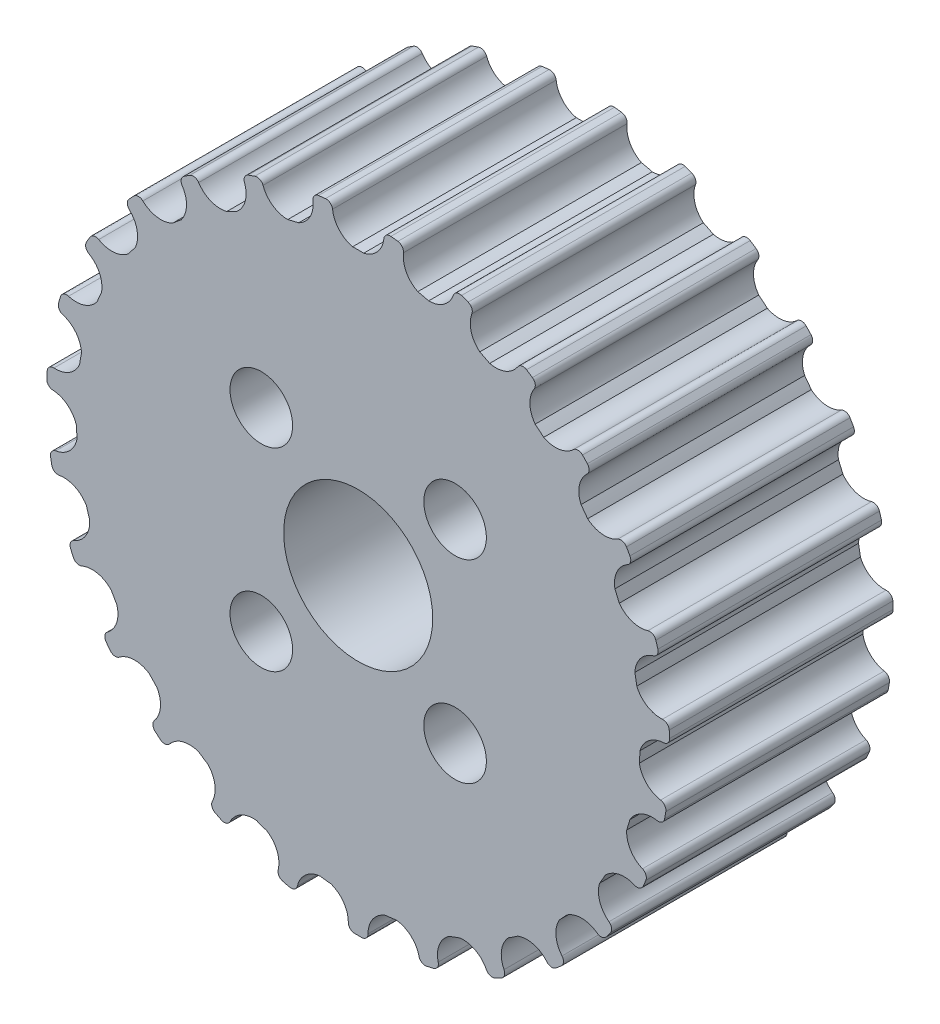
SolidWorks part; units mm, degrees
material "ABS"
ref_plane "Front Plane" through (0, 0, 0) normal (0, 0, 1) x (1, 0, 0)
ref_plane "Top Plane" through (0, 0, 0) normal (0, 1, 0) x (1, 0, 0)
ref_plane "Right Plane" through (0, 0, 0) normal (1, 0, 0) x (0, 0, -1)
ref_plane "Plane1" through (0, 0, 7.5) normal (0, 0, 1) x (1, 0, 0)
sketch "Sketch1" plane through (0, 0, 7.5) normal (0, 0, 1) x (1, 0, 0)
  arc A0 (-2.1927, 20.7989) -> (-2.663, 20.7439) centre (0, 0) ccw
  arc A1 (-2.663, 20.7439) -> (-3.0351, 20.266) centre (-2.6082, 20.3174) ccw
  arc A2 (-3.0351, 20.266) -> (-3.9982, 18.4886) centre (-4.7708, 20.0568) cw
  arc A3 (-3.9982, 18.4886) -> (-4.7247, 18.3164) centre (0, 0) ccw
  arc A4 (-4.7247, 18.3164) -> (-6.3831, 19.4725) centre (-4.7381, 20.0646) cw
  arc A5 (-6.3831, 19.4725) -> (-6.9301, 19.7326) centre (-6.7876, 19.3269) ccw
  arc A6 (-6.9301, 19.7326) -> (-7.3751, 19.5706) centre (0, 0) ccw
  arc A7 (-7.3751, 19.5706) -> (-7.627, 19.0198) centre (-7.2234, 19.1683) ccw
  arc A8 (-7.627, 19.0198) -> (-8.1542, 17.0682) centre (-9.2676, 18.416) cw
  arc A9 (-8.1542, 17.0682) -> (-8.8214, 16.7331) centre (0, 0) ccw
  arc A10 (-8.8214, 16.7331) -> (-10.7017, 17.4756) centre (-9.2376, 18.431) cw
  arc A11 (-10.7017, 17.4756) -> (-11.294, 17.6025) centre (-11.0618, 17.2406) ccw
  arc A12 (-11.294, 17.6025) -> (-11.6896, 17.3423) centre (0, 0) ccw
  arc A13 (-11.6896, 17.3423) -> (-11.8077, 16.7482) centre (-11.4492, 16.9857) ccw
  arc A14 (-11.8077, 16.7482) -> (-11.8706, 14.7276) centre (-13.2649, 15.7823) cw
  arc A15 (-11.8706, 14.7276) -> (-12.4425, 14.2477) centre (0, 0) ccw
  arc A16 (-12.4425, 14.2477) -> (-14.4433, 14.5366) centre (-13.2391, 15.8039) cw
  arc A17 (-14.4433, 14.5366) -> (-15.049, 14.5235) centre (-14.7395, 14.2248) ccw
  arc A18 (-15.049, 14.5235) -> (-15.3739, 14.179) centre (0, 0) ccw
  arc A19 (-15.3739, 14.179) -> (-15.3518, 13.5737) centre (-15.0578, 13.8875) ccw
  arc A20 (-15.3518, 13.5737) -> (-14.947, 11.5931) centre (-16.5469, 12.2978) cw
  arc A21 (-14.947, 11.5931) -> (-15.3929, 10.9942) centre (0, 0) ccw
  arc A22 (-15.3929, 10.9942) -> (-17.4064, 10.8139) centre (-16.5269, 12.3248) cw
  arc A23 (-17.4064, 10.8139) -> (-17.9926, 10.6614) centre (-17.6227, 10.4422) ccw
  arc A24 (-17.9926, 10.6614) -> (-18.2294, 10.2514) centre (0, 0) ccw
  arc A25 (-18.2294, 10.2514) -> (-18.0683, 9.6674) centre (-17.8546, 10.0406) ccw
  arc A26 (-18.0683, 9.6674) -> (-17.2177, 7.8335) centre (-18.937, 8.1503) cw
  arc A27 (-17.2177, 7.8335) -> (-17.5134, 7.148) centre (0, 0) ccw
  arc A28 (-17.5134, 7.148) -> (-19.431, 6.5082) centre (-18.9237, 8.1812) cw
  arc A29 (-19.431, 6.5082) -> (-19.9664, 6.2247) centre (-19.5558, 6.0967) ccw
  arc A30 (-19.9664, 6.2247) -> (-20.1022, 5.7711) centre (0, 0) ccw
  arc A31 (-20.1022, 5.7711) -> (-19.8107, 5.24) centre (-19.6889, 5.6524) ccw
  arc A32 (-19.8107, 5.24) -> (-18.5601, 3.6517) centre (-20.3061, 3.5635) cw
  arc A33 (-18.5601, 3.6517) -> (-18.6898, 2.9164) centre (0, 0) ccw
  arc A34 (-18.6898, 2.9164) -> (-20.4082, 1.8516) centre (-20.3003, 3.5966) cw
  arc A35 (-20.4082, 1.8516) -> (-20.8637, 1.4523) centre (-20.4347, 1.4225) ccw
  arc A36 (-20.8637, 1.4523) -> (-20.8912, 0.9796) centre (0, 0) ccw
  arc A37 (-20.8912, 0.9796) -> (-20.4851, 0.5301) centre (-20.4617, 0.9595) ccw
  arc A38 (-20.4851, 0.5301) -> (-18.902, -0.727) centre (-20.5806, -1.2155) cw
  arc A39 (-18.902, -0.727) -> (-18.8586, -1.4723) centre (0, 0) ccw
  arc A40 (-18.8586, -1.4723) -> (-20.2851, -2.9047) centre (-20.5825, -1.182) cw
  arc A41 (-20.2851, -2.9047) -> (-20.6362, -3.3983) centre (-20.2119, -3.3284) ccw
  arc A42 (-20.6362, -3.3983) -> (-20.554, -3.8646) centre (0, 0) ccw
  arc A43 (-20.554, -3.8646) -> (-20.0552, -4.2084) centre (-20.1314, -3.7852) ccw
  arc A44 (-20.0552, -4.2084) -> (-18.2248, -5.0665) centre (-19.7455, -5.929) cw
  arc A45 (-18.2248, -5.0665) -> (-18.0107, -5.7817) centre (0, 0) ccw
  arc A46 (-18.0107, -5.7817) -> (-19.0684, -7.5045) centre (-19.7551, -5.8968) cw
  arc A47 (-19.0684, -7.5045) -> (-19.2963, -8.0657) centre (-18.8995, -7.8999) ccw
  arc A48 (-19.2963, -8.0657) -> (-19.1087, -8.5005) centre (0, 0) ccw
  arc A49 (-19.1087, -8.5005) -> (-18.5441, -8.72) centre (-18.7158, -8.3258) ccw
  arc A50 (-18.5441, -8.72) -> (-16.5652, -9.1328) centre (-17.8459, -10.3228) cw
  arc A51 (-16.5652, -9.1328) -> (-16.1918, -9.7794) centre (0, 0) ccw
  arc A52 (-16.1918, -9.7794) -> (-16.8238, -11.6997) centre (-17.8627, -10.2937) cw
  arc A53 (-16.8238, -11.6997) -> (-16.916, -12.2984) centre (-16.5682, -12.0455) ccw
  arc A54 (-16.916, -12.2984) -> (-16.6333, -12.6782) centre (0, 0) ccw
  arc A55 (-16.6333, -12.6782) -> (-16.0333, -12.7615) centre (-16.2913, -12.4175) ccw
  arc A56 (-16.0333, -12.7615) -> (-14.0125, -12.7068) centre (-14.9843, -14.1601) cw
  arc A57 (-14.0125, -12.7068) -> (-13.5001, -13.2499) centre (0, 0) ccw
  arc A58 (-13.5001, -13.2499) -> (-13.6722, -15.2641) centre (-15.0074, -14.1356) cw
  arc A59 (-13.6722, -15.2641) -> (-13.6239, -15.868) centre (-13.3438, -15.5417) ccw
  arc A60 (-13.6239, -15.868) -> (-13.2611, -16.1723) centre (0, 0) ccw
  arc A61 (-13.2611, -16.1723) -> (-12.6581, -16.115) centre (-12.9885, -15.8398) ccw
  arc A62 (-12.6581, -16.115) -> (-10.7044, -15.5958) centre (-11.3149, -17.234) cw
  arc A63 (-10.7044, -15.5958) -> (-10.0806, -16.0061) centre (0, 0) ccw
  arc A64 (-10.0806, -16.0061) -> (-9.7835, -18.0057) centre (-11.3429, -17.2155) cw
  arc A65 (-9.7835, -18.0057) -> (-9.5972, -18.5821) centre (-9.3999, -18.2001) ccw
  arc A66 (-9.5972, -18.5821) -> (-9.1741, -18.7946) centre (0, 0) ccw
  arc A67 (-9.1741, -18.7946) -> (-8.6005, -18.5998) centre (-8.9855, -18.4082) ccw
  arc A68 (-8.6005, -18.5998) -> (-6.8192, -17.644) centre (-7.0354, -19.3788) cw
  arc A69 (-6.8192, -17.644) -> (-6.1176, -17.8994) centre (0, 0) ccw
  arc A70 (-6.1176, -17.8994) -> (-5.3674, -19.7766) centre (-7.067, -19.3674) cw
  arc A71 (-5.3674, -19.7766) -> (-5.0532, -20.2945) centre (-4.9493, -19.8772) ccw
  arc A72 (-5.0532, -20.2945) -> (-4.5925, -20.4037) centre (0, 0) ccw
  arc A73 (-4.5925, -20.4037) -> (-4.0793, -20.0819) centre (-4.498, -19.9842) ccw
  arc A74 (-4.0793, -20.0819) -> (-2.5664, -18.7411) centre (-2.3767, -20.479) cw
  arc A75 (-2.5664, -18.7411) -> (-1.8248, -18.8277) centre (0, 0) ccw
  arc A76 (-1.8248, -18.8277) -> (-0.6619, -20.4813) centre (-2.4101, -20.4751) cw
  arc A77 (-0.6619, -20.4813) -> (-0.2368, -20.9128) centre (-0.2319, -20.4828) ccw
  arc A78 (-0.2368, -20.9128) -> (0.2368, -20.9128) centre (0, 0) ccw
  arc A79 (0.2368, -20.9128) -> (0.6619, -20.4813) centre (0.2319, -20.4828) ccw
  arc A80 (0.6619, -20.4813) -> (1.8248, -18.8277) centre (2.4101, -20.4751) cw
  arc A81 (1.8248, -18.8277) -> (2.5664, -18.7411) centre (0, 0) ccw
  arc A82 (2.5664, -18.7411) -> (4.0793, -20.0819) centre (2.3767, -20.479) cw
  arc A83 (4.0793, -20.0819) -> (4.5925, -20.4037) centre (4.498, -19.9842) ccw
  arc A84 (4.5925, -20.4037) -> (5.0532, -20.2945) centre (0, 0) ccw
  arc A85 (5.0532, -20.2945) -> (5.3674, -19.7766) centre (4.9493, -19.8772) ccw
  arc A86 (5.3674, -19.7766) -> (6.1176, -17.8994) centre (7.067, -19.3674) cw
  arc A87 (6.1176, -17.8994) -> (6.8192, -17.644) centre (0, 0) ccw
  arc A88 (6.8192, -17.644) -> (8.6005, -18.5998) centre (7.0354, -19.3788) cw
  arc A89 (8.6005, -18.5998) -> (9.1741, -18.7946) centre (8.9855, -18.4082) ccw
  arc A90 (9.1741, -18.7946) -> (9.5972, -18.5821) centre (0, 0) ccw
  arc A91 (9.5972, -18.5821) -> (9.7835, -18.0057) centre (9.3999, -18.2001) ccw
  arc A92 (9.7835, -18.0057) -> (10.0806, -16.0061) centre (11.3429, -17.2155) cw
  arc A93 (10.0806, -16.0061) -> (10.7044, -15.5958) centre (0, 0) ccw
  arc A94 (10.7044, -15.5958) -> (12.6581, -16.115) centre (11.3149, -17.234) cw
  arc A95 (12.6581, -16.115) -> (13.2611, -16.1723) centre (12.9885, -15.8398) ccw
  arc A96 (13.2611, -16.1723) -> (13.6239, -15.868) centre (0, 0) ccw
  arc A97 (13.6239, -15.868) -> (13.6722, -15.2641) centre (13.3438, -15.5417) ccw
  arc A98 (13.6722, -15.2641) -> (13.5001, -13.2499) centre (15.0074, -14.1356) cw
  arc A99 (13.5001, -13.2499) -> (14.0125, -12.7068) centre (0, 0) ccw
  arc A100 (14.0125, -12.7068) -> (16.0333, -12.7615) centre (14.9843, -14.1601) cw
  arc A101 (16.0333, -12.7615) -> (16.6333, -12.6782) centre (16.2913, -12.4175) ccw
  arc A102 (16.6333, -12.6782) -> (16.916, -12.2984) centre (0, 0) ccw
  arc A103 (16.916, -12.2984) -> (16.8238, -11.6997) centre (16.5682, -12.0455) ccw
  arc A104 (16.8238, -11.6997) -> (16.1918, -9.7794) centre (17.8627, -10.2937) cw
  arc A105 (16.1918, -9.7794) -> (16.5652, -9.1328) centre (0, 0) ccw
  arc A106 (16.5652, -9.1328) -> (18.5441, -8.72) centre (17.8459, -10.3228) cw
  arc A107 (18.5441, -8.72) -> (19.1087, -8.5005) centre (18.7158, -8.3258) ccw
  arc A108 (19.1087, -8.5005) -> (19.2963, -8.0657) centre (0, 0) ccw
  arc A109 (19.2963, -8.0657) -> (19.0684, -7.5045) centre (18.8995, -7.8999) ccw
  arc A110 (19.0684, -7.5045) -> (18.0107, -5.7817) centre (19.7551, -5.8968) cw
  arc A111 (18.0107, -5.7817) -> (18.2248, -5.0665) centre (0, 0) ccw
  arc A112 (18.2248, -5.0665) -> (20.0552, -4.2084) centre (19.7455, -5.929) cw
  arc A113 (20.0552, -4.2084) -> (20.554, -3.8646) centre (20.1314, -3.7852) ccw
  arc A114 (20.554, -3.8646) -> (20.6362, -3.3983) centre (0, 0) ccw
  arc A115 (20.6362, -3.3983) -> (20.2851, -2.9047) centre (20.2119, -3.3284) ccw
  arc A116 (20.2851, -2.9047) -> (18.8586, -1.4723) centre (20.5825, -1.182) cw
  arc A117 (18.8586, -1.4723) -> (18.902, -0.727) centre (0, 0) ccw
  arc A118 (18.902, -0.727) -> (20.4851, 0.5301) centre (20.5806, -1.2155) cw
  arc A119 (20.4851, 0.5301) -> (20.8912, 0.9796) centre (20.4617, 0.9595) ccw
  arc A120 (20.8912, 0.9796) -> (20.8637, 1.4523) centre (0, 0) ccw
  arc A121 (20.8637, 1.4523) -> (20.4082, 1.8516) centre (20.4347, 1.4225) ccw
  arc A122 (20.4082, 1.8516) -> (18.6898, 2.9164) centre (20.3003, 3.5966) cw
  arc A123 (18.6898, 2.9164) -> (18.5601, 3.6517) centre (0, 0) ccw
  arc A124 (18.5601, 3.6517) -> (19.8107, 5.24) centre (20.3061, 3.5635) cw
  arc A125 (19.8107, 5.24) -> (20.1022, 5.7711) centre (19.6889, 5.6524) ccw
  arc A126 (20.1022, 5.7711) -> (19.9664, 6.2247) centre (0, 0) ccw
  arc A127 (19.9664, 6.2247) -> (19.431, 6.5082) centre (19.5558, 6.0967) ccw
  arc A128 (19.431, 6.5082) -> (17.5134, 7.148) centre (18.9237, 8.1812) cw
  arc A129 (17.5134, 7.148) -> (17.2177, 7.8335) centre (0, 0) ccw
  arc A130 (17.2177, 7.8335) -> (18.0683, 9.6674) centre (18.937, 8.1503) cw
  arc A131 (18.0683, 9.6674) -> (18.2294, 10.2514) centre (17.8546, 10.0406) ccw
  arc A132 (18.2294, 10.2514) -> (17.9926, 10.6614) centre (0, 0) ccw
  arc A133 (17.9926, 10.6614) -> (17.4064, 10.8139) centre (17.6227, 10.4422) ccw
  arc A134 (17.4064, 10.8139) -> (15.3929, 10.9942) centre (16.5269, 12.3248) cw
  arc A135 (15.3929, 10.9942) -> (14.947, 11.5931) centre (0, 0) ccw
  arc A136 (14.947, 11.5931) -> (15.3518, 13.5737) centre (16.5469, 12.2978) cw
  arc A137 (15.3518, 13.5737) -> (15.3739, 14.179) centre (15.0578, 13.8875) ccw
  arc A138 (15.3739, 14.179) -> (15.049, 14.5235) centre (0, 0) ccw
  arc A139 (15.049, 14.5235) -> (14.4433, 14.5366) centre (14.7395, 14.2248) ccw
  arc A140 (14.4433, 14.5366) -> (12.4425, 14.2477) centre (13.2391, 15.8039) cw
  arc A141 (12.4425, 14.2477) -> (11.8706, 14.7276) centre (0, 0) ccw
  arc A142 (11.8706, 14.7276) -> (11.8077, 16.7482) centre (13.2649, 15.7823) cw
  arc A143 (11.8077, 16.7482) -> (11.6896, 17.3423) centre (11.4492, 16.9857) ccw
  arc A144 (11.6896, 17.3423) -> (11.294, 17.6025) centre (0, 0) ccw
  arc A145 (11.294, 17.6025) -> (10.7017, 17.4756) centre (11.0618, 17.2406) ccw
  arc A146 (10.7017, 17.4756) -> (8.8214, 16.7331) centre (9.2376, 18.431) cw
  arc A147 (8.8214, 16.7331) -> (8.1542, 17.0682) centre (0, 0) ccw
  arc A148 (8.1542, 17.0682) -> (7.627, 19.0198) centre (9.2676, 18.416) cw
  arc A149 (7.627, 19.0198) -> (7.3751, 19.5706) centre (7.2234, 19.1683) ccw
  arc A150 (7.3751, 19.5706) -> (6.9301, 19.7326) centre (0, 0) ccw
  arc A151 (6.9301, 19.7326) -> (6.3831, 19.4725) centre (6.7876, 19.3269) ccw
  arc A152 (6.3831, 19.4725) -> (4.7247, 18.3164) centre (4.7381, 20.0646) cw
  arc A153 (4.7247, 18.3164) -> (3.9982, 18.4886) centre (0, 0) ccw
  arc A154 (3.9982, 18.4886) -> (3.0351, 20.266) centre (4.7708, 20.0568) cw
  arc A155 (3.0351, 20.266) -> (2.663, 20.7439) centre (2.6082, 20.3174) ccw
  arc A156 (2.663, 20.7439) -> (2.1927, 20.7989) centre (0, 0) ccw
  arc A157 (2.1927, 20.7989) -> (1.7203, 20.4197) centre (2.1476, 20.3713) ccw
  arc A158 (1.7203, 20.4197) -> (0.3733, 18.9123) centre (-0.0168, 20.6164) cw
  arc A159 (0.3733, 18.9123) -> (-0.3733, 18.9123) centre (0, 0) ccw
  arc A160 (-0.3733, 18.9123) -> (-1.7203, 20.4197) centre (0.0168, 20.6164) cw
  arc A161 (-1.7203, 20.4197) -> (-2.1927, 20.7989) centre (-2.1476, 20.3713) ccw
extrude "Boss-Extrude1" add sketch "Sketch1" against normal blind 15
sketch "Sketch2" plane through (0, 0, 7.5) normal (0, 0, 1) x (1, 0, 0)
  line L1 (-6.5, -6.5) -> (6.5, -6.5) construction
  line L2 (-6.5, -6.5) -> (-6.5, 6.5) construction
  line L3 (-6.5, 6.5) -> (6.5, 6.5) construction
  line L4 (6.5, -6.5) -> (6.5, 6.5) construction
  line L5 (-6.5, -6.5) -> (6.5, 6.5) construction
  line L6 (-6.5, 6.5) -> (6.5, -6.5) construction
  circle A1 centre (-6.5, 6.5) radius 2.1
  circle A2 centre (6.5, 6.5) radius 2.1
  circle A3 centre (6.5, -6.5) radius 2.1
  circle A4 centre (-6.5, -6.5) radius 2.1
  circle A5 centre (0, 0) radius 5
  point P0 (0, 0)
  dimension "D2" = 13
  dimension "D3" = 4.2
  dimension "D4" = 4.2
  dimension "D5" = 4.2
  dimension "D6" = 4.2
  dimension "D7" = 10
  dimension "D1" = 13
extrude "Cut-Extrude1" cut sketch "Sketch2" against normal through all
